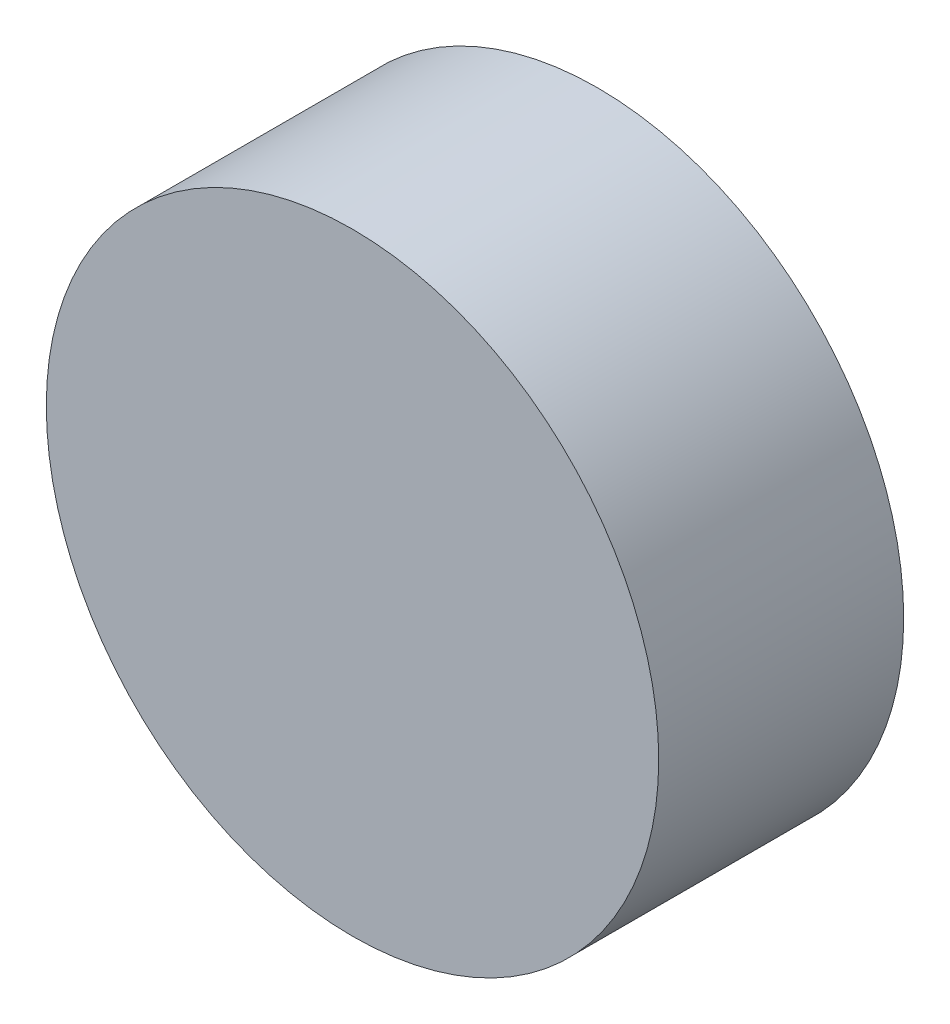
SolidWorks part; units mm, degrees
ref_plane "Front Plane" through (0, 0, 0) normal (0, 0, 1) x (1, 0, 0)
ref_plane "Top Plane" through (0, 0, 0) normal (0, 1, 0) x (1, 0, 0)
ref_plane "Right Plane" through (0, 0, 0) normal (1, 0, 0) x (0, 0, -1)
other "Configuration Table"
sketch "Sketch1" plane through (0, 0, 0) normal (0, 0, 1) x (1, 0, 0)
  circle A0 centre (0, 0) radius 15
extrude "MTG_kasnak_D30_kayis" add sketch "Sketch1" against normal blind 12 from offset 6 separate body
